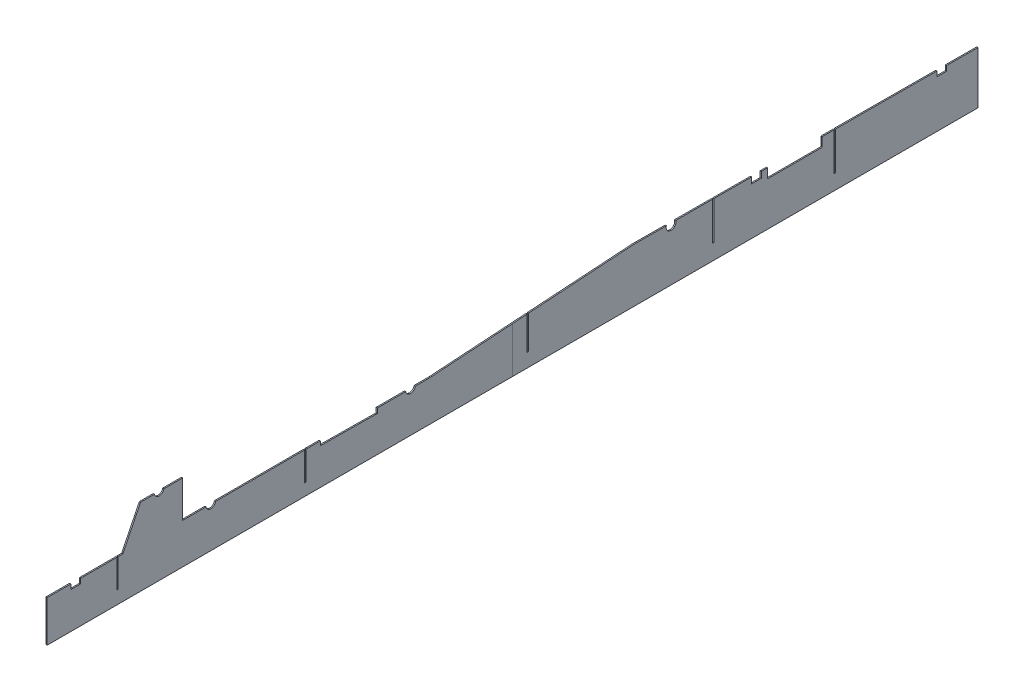
SolidWorks part; units mm, degrees
ref_plane "Front Plane" through (0, 0, 0) normal (0, 0, 1) x (1, 0, 0)
ref_plane "Top Plane" through (0, 0, 0) normal (0, 1, 0) x (1, 0, 0)
ref_plane "Right Plane" through (0, 0, 0) normal (1, 0, 0) x (0, 0, -1)
sketch "Sketch3" plane through (0, 0, 0) normal (1, 0, 0) x (0, 0, -1)
  line L0 (1727.2, 0) -> (1346.2, 1.8088)
  line L3 (-762, -139.7) -> (1727.2, -139.7)
  line L4 (1727.2, 0) -> (1727.2, -139.7)
  line L10 (807.5507, 4.366) -> (525.3228, -14.2775)
  line L14 (260.8208, -31.75) -> (-69.6468, -31.75)
  line L20 (-399.5792, -31.75) -> (-399.5792, 66.6583)
  line L27 (-575.5513, -29.3624) -> (-762, -29.3624)
  line L31 (-762, -139.7) -> (-762, -29.3624)
  line L34 (-399.5792, 66.6583) -> (-512.373, 66.6583)
  line L36 (1346.2, 1.8088) -> (1346.2, -99.7912)
  line L41 (1643.3038, 13.081) -> (1617.1418, 13.081)
  line L42 (1643.3038, 13.081) -> (1643.3038, -13.081)
  line L47 (1643.3038, -13.081) -> (1617.1418, -13.081)
  line L48 (1617.1418, 13.081) -> (1617.1418, -13.081)
  line L53 (1643.3038, 13.081) -> (1617.1418, -13.081) construction
  line L54 (1643.3038, -13.081) -> (1617.1418, 13.081) construction
  line L55 (1148.0038, 13.081) -> (1121.8418, 13.081)
  line L56 (1148.0038, 13.081) -> (1148.0038, -13.081)
  line L57 (1148.0038, -13.081) -> (1121.8418, -13.081)
  line L58 (1121.8418, 13.081) -> (1121.8418, -13.081)
  line L59 (1148.0038, 13.081) -> (1121.8418, -13.081) construction
  line L60 (1148.0038, -13.081) -> (1121.8418, 13.081) construction
  line L61 (-672.719, -16.2814) -> (-698.881, -16.2814)
  line L62 (-672.719, -16.2814) -> (-672.719, -42.4434)
  line L63 (-672.719, -42.4434) -> (-698.881, -42.4434)
  line L64 (-698.881, -16.2814) -> (-698.881, -42.4434)
  line L65 (-672.719, -16.2814) -> (-698.881, -42.4434) construction
  line L66 (-672.719, -42.4434) -> (-698.881, -16.2814) construction
  line L67 (1346.2, -99.7912) -> (1342.6186, -99.7912)
  line L68 (1342.6186, -99.7912) -> (1342.6186, 1.8258)
  line L69 (1342.6186, 1.8258) -> (1020.6228, 3.3544)
  line L70 (1020.6228, 3.3544) -> (1020.6228, -98.2456)
  line L71 (1020.6228, -98.2456) -> (1017.0414, -98.2456)
  line L72 (1017.0414, -98.2456) -> (1017.0414, 3.3714)
  line L73 (1017.0414, 3.3714) -> (807.5507, 4.366)
  line L77 (521.7414, -14.5141) -> (260.8208, -31.75)
  line L79 (525.3228, -14.2775) -> (525.3228, -103.1775)
  line L80 (525.3228, -103.1775) -> (521.7414, -103.1775)
  line L81 (521.7414, -103.1775) -> (521.7414, -14.5141)
  line L82 (-69.6468, -31.75) -> (-69.6468, -107.95)
  line L83 (-69.6468, -107.95) -> (-73.2282, -107.95)
  line L84 (-73.2282, -107.95) -> (-73.2282, -31.75)
  line L85 (-73.2282, -31.75) -> (-399.5792, -31.75)
  line L86 (-571.9699, -29.3624) -> (-571.9699, -105.5624)
  line L87 (-571.9699, -105.5624) -> (-575.5513, -105.5624)
  line L88 (-575.5513, -105.5624) -> (-575.5513, -29.3624)
  line L89 (-571.9699, -29.3624) -> (-559.8248, -29.3624)
  line L90 (-559.8248, -29.3624) -> (-512.373, 66.6583)
  circle A6 centre (906.3228, 0) radius 13.081
  circle A7 centre (209.7532, -29.3624) radius 13.081
  circle A8 centre (-324.3199, -29.3624) radius 13.081
  circle A9 centre (-462.4548, 69.4951) radius 13.081
  point P8 (1630.2228, 0)
  point P16 (1134.9228, 0)
  point P27 (-685.8, -29.3624)
  dimension "D8" = 26.162
  dimension "D9" = 26.162
  dimension "D10" = 26.162
  dimension "D3" = 107.95
  dimension "D6" = 26.162
  dimension "D15" = 101.6
  dimension "D12" = 26.162
  dimension "D14" = 26.162
  dimension "D1" = 2489.2
  dimension "D2" = 139.7
  dimension "D4" = 1727.2
  dimension "D5" = 762
  dimension "D7" = 139.7
  dimension "D11" = 660.4
  dimension "D13" = 26.162
  dimension "D16" = 381
  dimension "D17" = 3.5814
  dimension "D18" = 101.6
  dimension "D19" = 3.5814
  dimension "D20" = 114.3
  dimension "D21" = 88.9
  dimension "D22" = 3.5814
  dimension "D23" = 76.2
  dimension "D24" = 279.4
  dimension "D25" = 3.5814
  dimension "D26" = 76.2
  dimension "D27" = 3.5814
  dimension "D28" = 247.65
extrude "Boss-Extrude1" add sketch "Sketch3" along normal mid plane 3.175
sketch "Sketch5" plane through (1.5875, 0, 0) normal (1, 0, 0) x (0, 0, -1)
  line L0 (1342.6186, 1.8258) -> (1148.0038, 2.7497) construction
  line L1 (1310.5638, 1.978) -> (1164.5138, 2.6713)
  line L2 (1148.0038, 2.7497) -> (1148.0038, -13.081) construction
  line L3 (1148.0038, 2.7497) -> (1148.0038, -13.081)
  line L4 (1164.5138, 2.6713) -> (1164.5138, -22.7287)
  line L5 (1164.5138, -22.7287) -> (1310.5638, -22.7287)
  line L6 (1310.5638, -22.7287) -> (1310.5638, 1.978)
  line L7 (120.8532, -31.75) -> (120.8532, -44.45)
  line L8 (196.8919, -31.75) -> (-69.6468, -31.75) construction
  line L9 (-31.5468, -31.75) -> (-31.5468, -42.8572)
  line L10 (120.8532, -31.75) -> (-31.5468, -31.75)
  line L11 (120.8532, -44.45) -> (-31.5468, -42.8572)
  line L12 (-69.6468, -31.75) -> (-69.6468, -107.95) construction
  line L13 (-69.6468, -31.75) -> (-69.6468, -107.95)
  line M29 (1342.6186, 1.8258) -> (1148.0038, 2.7497)
  dimension "D1" = 25.4
  dimension "D2" = 16.51
  dimension "D3" = 146.05
  dimension "D4" = 152.4
  dimension "D5" = 12.7
  dimension "D6" = 38.1
extrude "Cut-Extrude5" cut sketch "Sketch5" against normal through all contours L5 L6 L4 M29 | L11 L9 L10 L7
sketch "Sketch6" plane through (-1.5875, 0, 0) normal (-1, 0, 0) x (0, 0, 1)
  line L0 (762, -139.7) -> (-1727.2, -139.7) construction
  line L1 (762, -139.7) -> (-1727.2, -139.7)
  line L2 (-482.6, -139.7) -> (-482.6, -17.0997)
  line L3 (-521.7414, -14.5141) -> (-260.8208, -31.75) construction
split line "Split Line1"
sketch "Sketch7" plane through (1.5875, 0, 0) normal (1, 0, 0) x (0, 0, -1)
  line L0 (482.6, -139.7) -> (482.6, -17.0997) construction
  line L1 (-762, -139.7) -> (1727.2, -139.7) construction
  line L2 (482.6, -139.7) -> (482.6, -17.0997)
  line L3 (-762, -139.7) -> (1727.2, -139.7)
split line "Split Line2"
